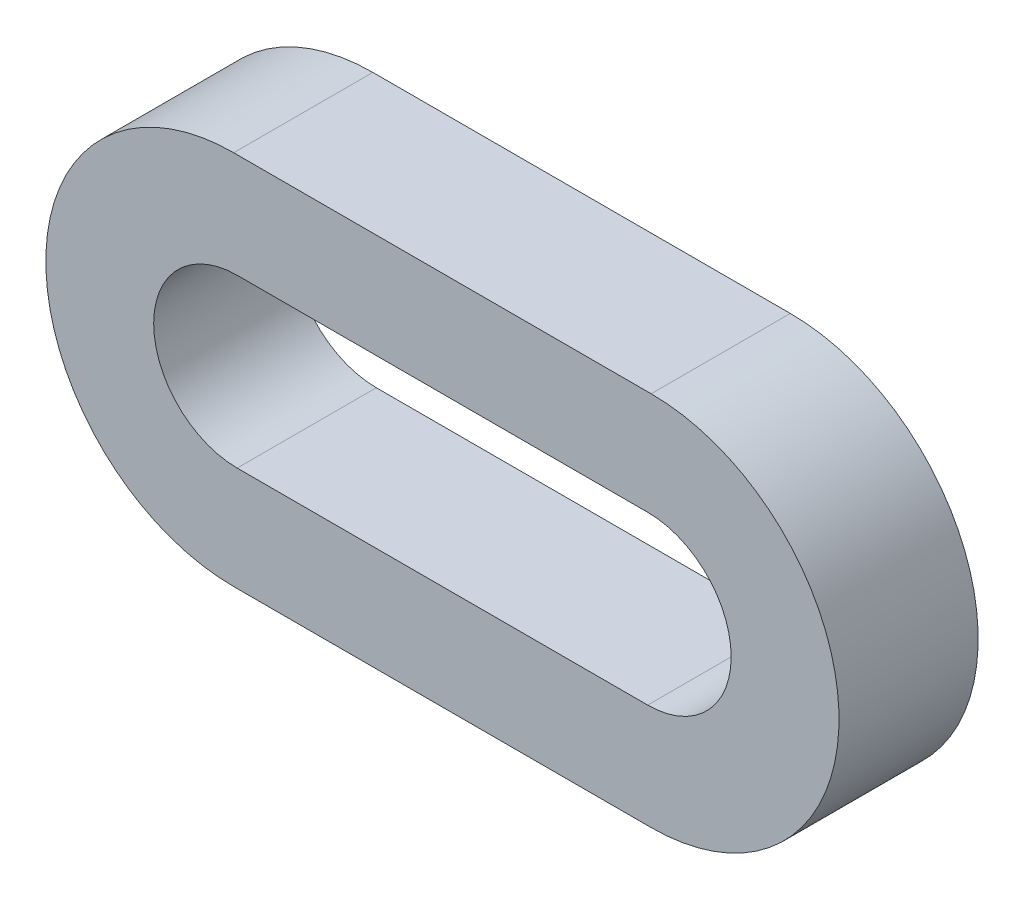
SolidWorks part; units mm, degrees
material "ABS"
ref_plane "Front Plane" through (0, 0, 0) normal (0, 0, 1) x (1, 0, 0)
ref_plane "Top Plane" through (0, 0, 0) normal (0, 1, 0) x (1, 0, 0)
ref_plane "Right Plane" through (0, 0, 0) normal (1, 0, 0) x (0, 0, -1)
sketch "ProfileS" plane through (0, 0, 0) normal (0, 0, 1) x (1, 0, 0)
  line L0 (-3, 0) -> (3, 0) construction
  line L1 (-3, 3.2) -> (3, 3.2) construction
  line L2 (-3, -3.2) -> (3, -3.2) construction
  line L3 (-3, 2.7) -> (3, 2.7)
  line L4 (-3, -2.7) -> (3, -2.7)
  arc A0 (-3, 3.2) -> (-3, -3.2) centre (-3, 0) ccw construction
  arc A1 (3, -3.2) -> (3, 3.2) centre (3, 0) ccw construction
  arc A2 (3, -2.7) -> (3, 2.7) centre (3, 0) ccw
  arc A3 (-3, 2.7) -> (-3, -2.7) centre (-3, 0) ccw
  point P2 (0, 0)
  point P8 (-6.2, 0)
  point P9 (6.2, 0)
  dimension "RefHeight" = 6.4
  dimension "RefWidth" = 12.4
  dimension "InsertionDimControl" = 0.5
extrude "Profile" add sketch "ProfileS" along normal mid plane 2
sketch "USBCCutoutS" plane through (0, 0, 0) normal (0, 0, 1) x (1, 0, 0)
  line L0 (-2.95, 0) -> (2.95, 0) construction
  line L1 (-2.95, 1.2) -> (2.95, 1.2)
  line L2 (-2.95, -1.2) -> (2.95, -1.2)
  arc A0 (-2.95, 1.2) -> (-2.95, -1.2) centre (-2.95, 0) ccw
  arc A1 (2.95, -1.2) -> (2.95, 1.2) centre (2.95, 0) ccw
  point P2 (0, 0)
  point P8 (-4.15, 0)
  point P9 (4.15, 0)
  dimension "Height" = 2.4
  dimension "Width" = 8.3
extrude "USBCCutout" cut sketch "USBCCutoutS" against normal through all both and the other way through all
